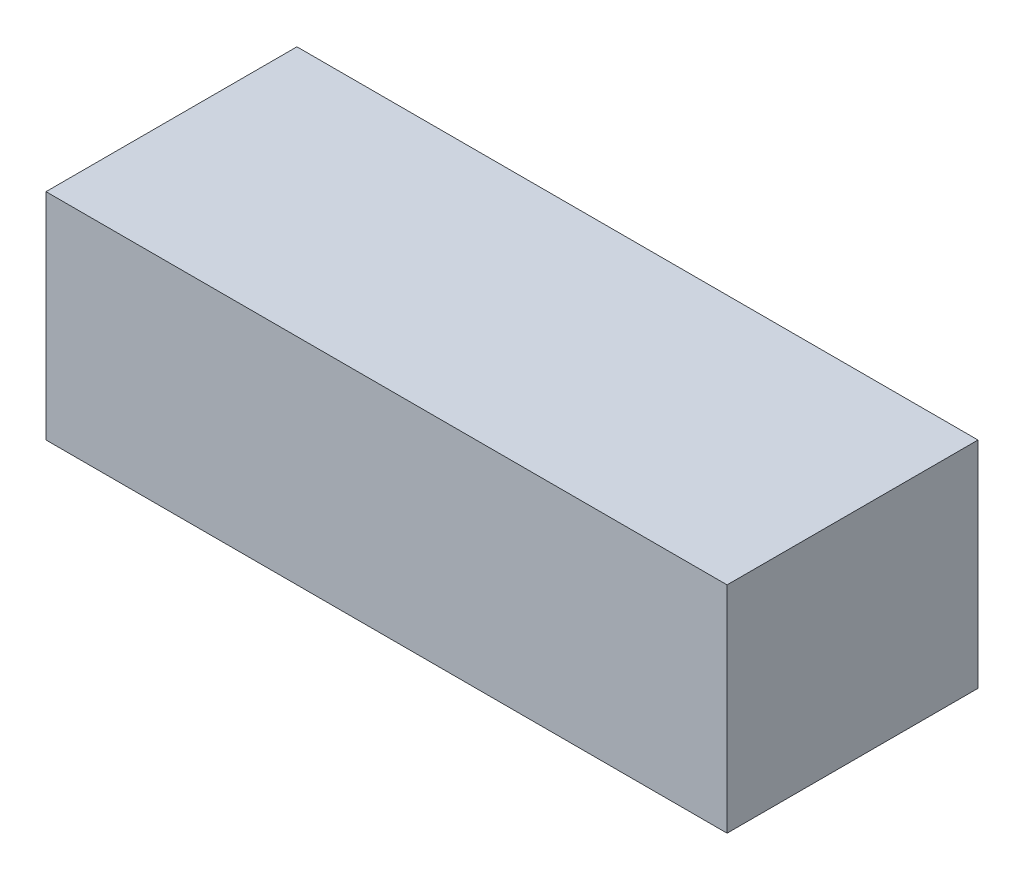
SolidWorks part; units mm, degrees
ref_plane "Front Plane" through (0, 0, 0) normal (0, 0, 1) x (1, 0, 0)
ref_plane "Top Plane" through (0, 0, 0) normal (0, 1, 0) x (1, 0, 0)
ref_plane "Right Plane" through (0, 0, 0) normal (1, 0, 0) x (0, 0, -1)
sketch "Sketch1" plane through (0, 0, 0) normal (0, 1, 0) x (1, 0, 0)
  line L1 (0, 0) -> (152, 0)
  line L2 (0, 0) -> (0, 56)
  line L3 (0, 56) -> (152, 56)
  line L4 (152, 0) -> (152, 56)
  dimension "D1" = 152
  dimension "D2" = 56
extrude "Boss-Extrude1" add sketch "Sketch1" along normal blind 48
